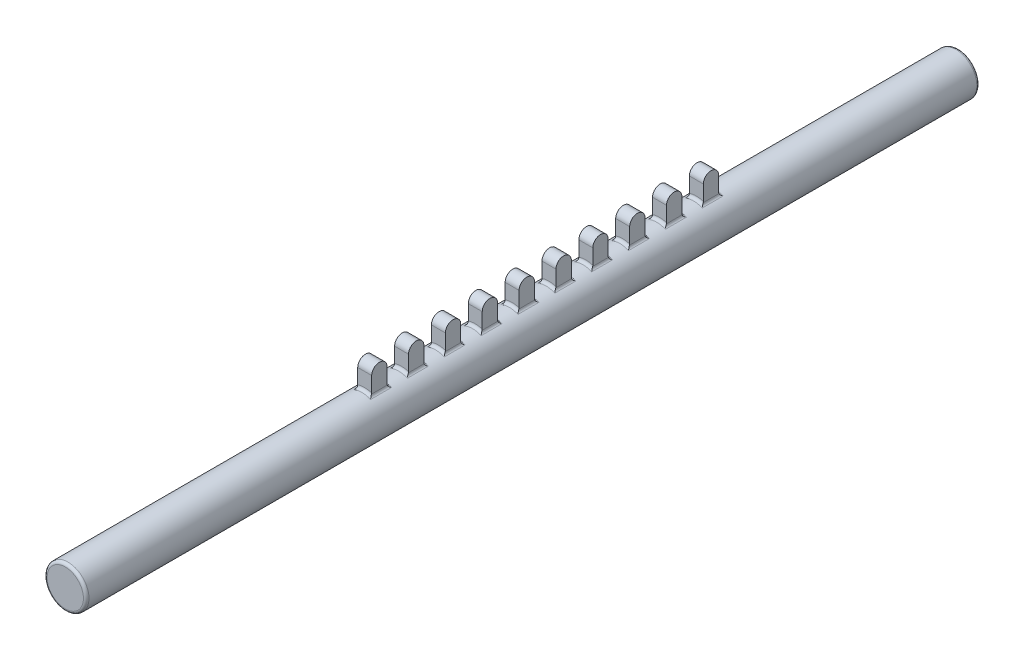
SolidWorks part; units mm, degrees
ref_plane "Front Plane" through (0, 0, 0) normal (0, 0, 1) x (1, 0, 0)
ref_plane "Top Plane" through (0, 0, 0) normal (0, 1, 0) x (1, 0, 0)
ref_plane "Right Plane" through (0, 0, 0) normal (1, 0, 0) x (0, 0, -1)
sketch "Sketch1" plane through (0, 0, 0) normal (0, 0, 1) x (1, 0, 0)
  circle A0 centre (0, 0) radius 7.5
  dimension "D1" = 15
extrude "Boss-Extrude1" add sketch "Sketch1" against normal blind 120 and the other way blind 200
sketch "Sketch3" plane through (0, 0, 0) normal (1, 0, 0) x (0, 0, -1)
  line L0 (0, 0) -> (-200, 0) construction
  line L1 (-200, 7.5) -> (-200, -7.5) construction
  line L2 (-90, 0) -> (-90, 33.1022) construction
  line L3 (-92.75, 0) -> (-92.75, 13.5)
  line L4 (-87.25, 13.5) -> (-87.25, 0)
  line L5 (120, 7.5) -> (-200, 7.5) construction
  line L6 (-92.75, 0) -> (-87.25, 0)
  arc A0 (-92.75, 13.5) -> (-87.25, 13.5) centre (-90, 13.5) cw
  dimension "D2" = 2.75
  dimension "D1" = 90
  dimension "D3" = 6
extrude "Boss-Extrude2" add sketch "Sketch3" along normal mid plane 5
pattern_linear "LPattern1" count 10 spacing 13.2 along (0, 0, -1) of "Boss-Extrude2"
fillet "Fillet1" radius 1 42 edges at (0, 7.5, -31.55) (-2.5, 7.0711, -28.8) (0, 7.5, -26.05) (2.5, 7.0711, -28.8) (0, 7.5, -5.15) (-2.5, 7.0711, -2.4) (0, 7.5, 0.35) (2.5, 7.0711, -2.4) (0, 7.5, 21.25) (-2.5, 7.0711, 24) (0, 7.5, 26.75) (2.5, 7.0711, 24) (0, 7.5, 47.65) (-2.5, 7.0711, 50.4) (0, 7.5, 53.15) (2.5, 7.0711, 50.4) (0, 7.5, 74.05) (-2.5, 7.0711, 76.8) (0, 7.5, 79.55) (2.5, 7.0711, 76.8) (7.5, 0, -120) (7.5, 0, 200) (0, 7.5, 87.25) (-2.5, 7.0711, 90) (0, 7.5, 92.75) (2.5, 7.0711, 90) (0, 7.5, 60.85) (-2.5, 7.0711, 63.6) (0, 7.5, 66.35) (2.5, 7.0711, 63.6) (0, 7.5, 34.45) (-2.5, 7.0711, 37.2) (0, 7.5, 39.95) (2.5, 7.0711, 37.2) (0, 7.5, 8.05) (-2.5, 7.0711, 10.8) (0, 7.5, 13.55) (2.5, 7.0711, 10.8) (0, 7.5, -18.35) (-2.5, 7.0711, -15.6) (0, 7.5, -12.85) (2.5, 7.0711, -15.6)
